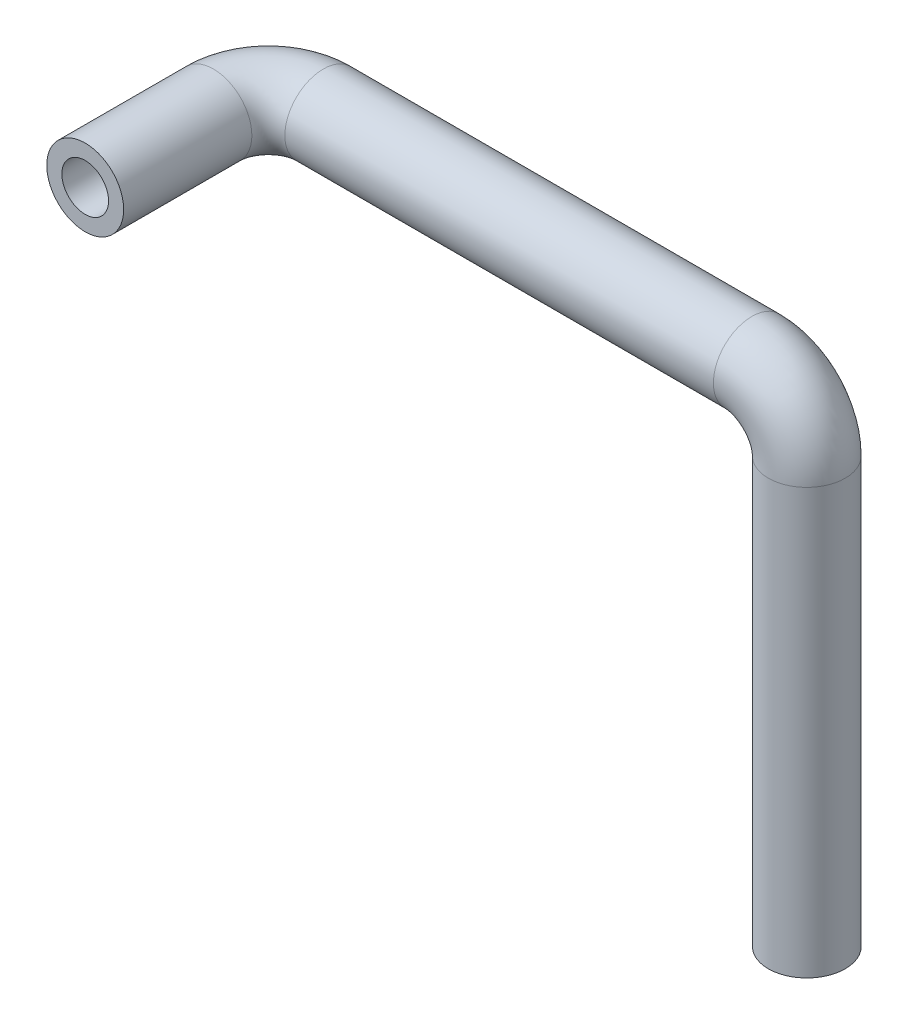
SolidWorks part; units mm, degrees
ref_plane "Ön Düzlem" through (0, 0, 0) normal (0, 0, 1) x (1, 0, 0)
ref_plane "Üst Düzlem" through (0, 0, 0) normal (0, 1, 0) x (1, 0, 0)
ref_plane "Sağ Düzlem" through (0, 0, 0) normal (1, 0, 0) x (0, 0, -1)
sketch3d "3DSketch1"
  line L0 (0, 0, 0) -> (0, 116, 0)
  line L1 (-15, 131, 0) -> (-132, 131, 0)
  line L2 (-147, 131, 15) -> (-147, 131, 50)
  arc A0 (-132, 131, 0) -> (-147, 131, 15) centre (-132, 131, 15) ccw
  arc A1 (0, 116, 0) -> (-15, 131, 0) centre (-15, 116, 0) ccw
  point P7 (-147, 131, 0)
  point P8 (-132, 146, 15)
  point P11 (0, 131, 0)
  point P12 (-15, 116, 15)
  dimension "D4" = 15
  dimension "D1" = 131
  dimension "D2" = 147
  dimension "D3" = 50
sketch "Sketch1" plane through (0, 0, 0) normal (0, 1, 0) x (1, 0, 0)
  circle A0 centre (0, 0) radius 6.375
  circle A1 centre (0, 0) radius 10.5
  dimension "D1" = 21
  dimension "D2" = 12.75
sweep "Sweep1" add profiles "Sketch1" path "3DSketch1"
